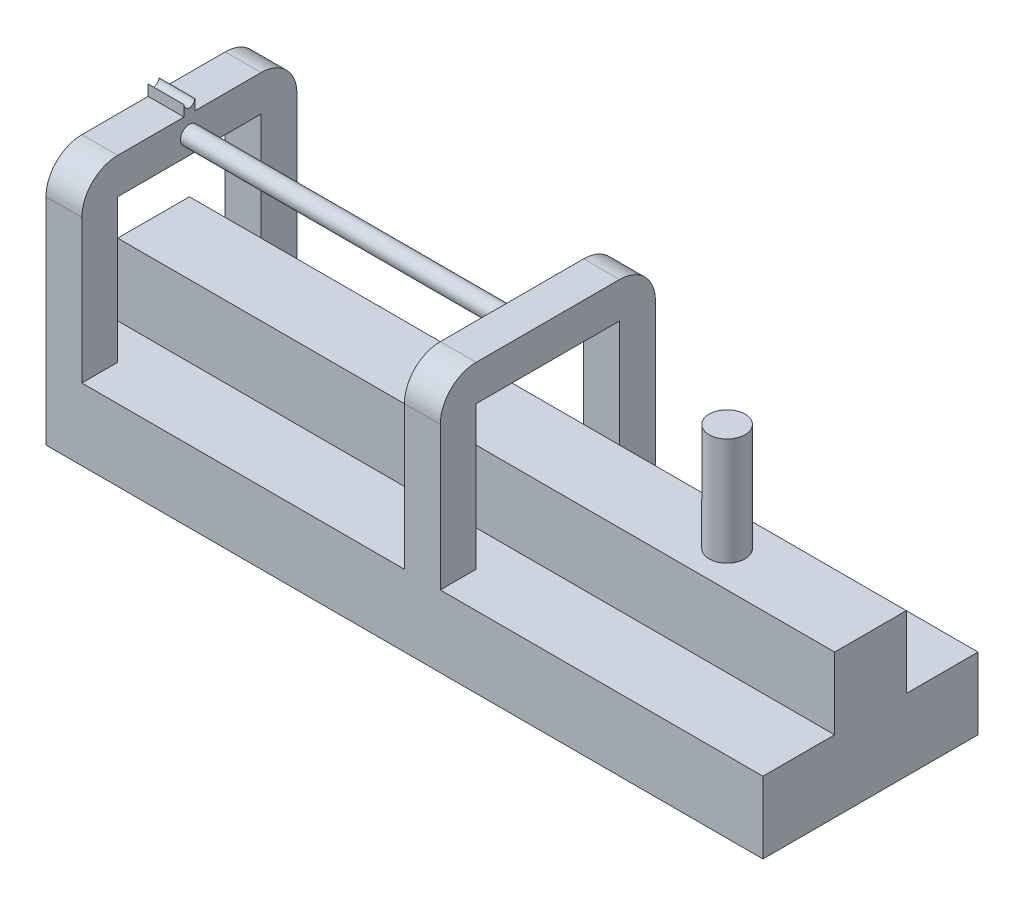
SolidWorks part; units mm, degrees
ref_plane "정면" through (0, 0, 0) normal (0, 0, 1) x (1, 0, 0)
ref_plane "윗면" through (0, 0, 0) normal (0, 1, 0) x (1, 0, 0)
ref_plane "우측면" through (0, 0, 0) normal (1, 0, 0) x (0, 0, -1)
sketch "스케치1" plane through (0, 0, 0) normal (1, 0, 0) x (0, 0, -1)
  line L9 (0, 0) -> (0, 45.1163) construction
  line L10 (30, 0) -> (-30, 0)
  line L11 (-30, 0) -> (-30, 20)
  line L12 (30, 0) -> (30, 20)
  line L13 (-30, 20) -> (-10, 20)
  line L14 (30, 20) -> (10, 20)
  line L15 (-10, 20) -> (-10, 40)
  line L16 (10, 20) -> (10, 40)
  line L17 (-10, 40) -> (10, 40)
  point P10 (0, 40)
  dimension "D1" = 20
  dimension "D2" = 20
  dimension "D3" = 20
  dimension "D4" = 60
extrude "보스-돌출1" add sketch "스케치1" along normal blind 200
sketch "스케치2" plane through (0, 0, 0) normal (-1, 0, 0) x (0, 0, 1)
  line L0 (30, 20) -> (30, 0) construction
  line L1 (-30, 20) -> (-20, 20)
  line L2 (-30, 20) -> (-30, 70)
  line L3 (-30, 70) -> (30, 70)
  line L4 (30, 20) -> (30, 70)
  line L6 (-20, 20) -> (-20, 60)
  line L7 (-20, 60) -> (20, 60)
  line L8 (20, 20) -> (20, 60)
  line L9 (20, 20) -> (30, 20)
  dimension "D1" = 10
  dimension "D2" = 10
  dimension "D3" = 10
  dimension "D4" = 50
extrude "보스-돌출2" add sketch "스케치2" against normal blind 10
ref_plane "평면1" through (100, 0, 0) normal (-1, 0, 0) x (0, 0, 1)
sketch "스케치3" plane through (100, 0, 0) normal (-1, 0, 0) x (0, 0, 1)
  line L0 (20, 20) -> (30, 20)
  line L1 (-30, 20) -> (-20, 20)
  line L2 (-30, 20) -> (-30, 70)
  line L3 (-30, 70) -> (30, 70)
  line L4 (30, 20) -> (30, 70)
  line L6 (-20, 20) -> (-20, 60)
  line L7 (-20, 60) -> (20, 60)
  line L8 (20, 20) -> (20, 60)
extrude "보스-돌출3" add sketch "스케치3" against normal blind 10
fillet "필렛1" radius 10 4 edges at (5, 70, 30) (5, 70, -30) (105, 70, 30) (105, 70, -30)
sketch "스케치4" plane through (10, 0, 0) normal (1, 0, 0) x (0, 0, -1)
  line L0 (-20, 70) -> (20, 70) construction
  circle A0 centre (0, 65) radius 2.5
  dimension "D2" = 5
  dimension "D1" = 5
extrude "보스-돌출4" add sketch "스케치4" along normal up to next
sketch "스케치5" plane through (0, 40, 0) normal (0, 1, 0) x (1, 0, 0)
  line L0 (200, 10) -> (200, -10) construction
  circle A0 centre (160, 0) radius 5
  point P5 (200, 0)
  dimension "D1" = 10
  dimension "D2" = 40
extrude "보스-돌출5" add sketch "스케치5" along normal up to surface (30 mm away) up to face at (105, 70, 0)
sketch "스케치6" plane through (0, 0, 0) normal (-1, 0, 0) x (0, 0, 1)
  line L0 (-1.5, 73) -> (-1.5, 70)
  line L1 (20, 70) -> (-20, 70) construction
  line L2 (-1.5, 70) -> (1.5, 70)
  line L3 (1.5, 70) -> (1.5, 73)
  circle A0 centre (0, 73) radius 1.5 construction
  arc A1 (-1.5, 73) -> (1.5, 73) centre (0, 73) ccw
extrude "보스-돌출6" add sketch "스케치6" against normal blind 10
